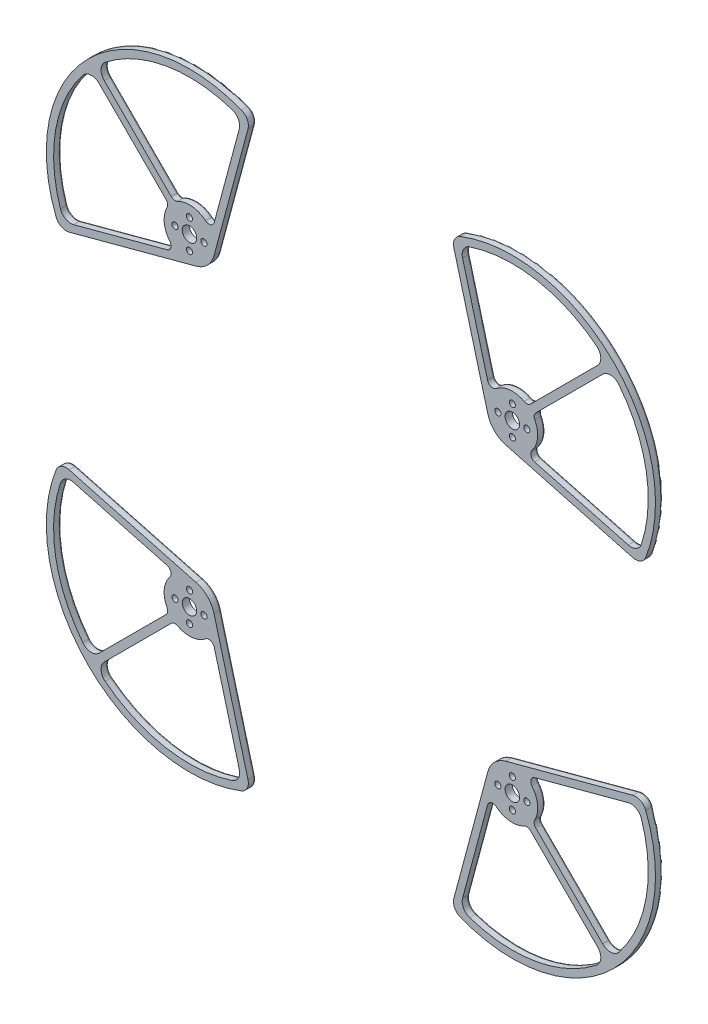
SolidWorks part; units mm, degrees
ref_plane "前视基准面" through (0, 0, 0) normal (0, 0, 1) x (1, 0, 0)
ref_plane "上视基准面" through (0, 0, 0) normal (0, 1, 0) x (1, 0, 0)
ref_plane "右视基准面" through (0, 0, 0) normal (1, 0, 0) x (0, 0, -1)
sketch "草图2" plane through (0, 0, -56.57) normal (0, 0, 1) x (1, 0, 0)
  line L0 (85.472, -75.5725) -> (160.5723, -55.4494)
  line L1 (0, 0) -> (89.0955, -89.0955) construction
  line L2 (75.5725, -85.472) -> (55.4494, -160.5723)
  line L3 (95.9714, -76.9003) -> (158.3049, -60.1981)
  line L4 (86.5073, -79.4362) -> (161.6076, -59.3131) construction
  line L5 (89.0955, -89.0955) -> (144.9569, -144.9569) construction
  line L6 (87.6812, -90.5097) -> (143.5248, -146.3532)
  line L7 (90.5097, -87.6812) -> (146.3532, -143.5248)
  line L8 (89.0955, -89.0955) -> (149.2055, -149.2055) construction
  line L9 (87.6812, -90.5097) -> (147.7913, -150.6197) construction
  line L10 (90.5097, -87.6812) -> (150.6197, -147.7913) construction
  line L11 (76.9003, -95.9714) -> (60.1981, -158.3049)
  circle A0 centre (89.0955, -89.0955) radius 75
  circle A1 centre (89.0955, -81.0955) radius 1.7 construction
  circle A2 centre (81.0955, -89.0955) radius 1.7 construction
  circle A3 centre (89.0955, -97.0955) radius 1.7 construction
  circle A4 centre (97.0955, -89.0955) radius 1.7 construction
  circle A5 centre (89.0955, -81.0955) radius 1.7
  circle A6 centre (81.0955, -89.0955) radius 1.7
  circle A7 centre (89.0955, -97.0955) radius 1.7
  circle A8 centre (97.0955, -89.0955) radius 1.7
  circle A9 centre (89.0955, -89.0955) radius 79
  circle A10 centre (89.0955, -89.0955) radius 14
  circle A11 centre (89.0955, -89.0955) radius 4 construction
  circle A12 centre (89.0955, -89.0955) radius 4
  dimension "D1" = 150
  dimension "D3" = 120
  dimension "D2" = 4
  dimension "D4" = 4
  dimension "D5" = 2
  dimension "D6" = 2
extrude "凸台-拉伸1" add sketch "草图2" along normal blind 4 contours A10 L3 A0 L0 | A10 L6 A0 L7 | A12 L7 A10 L6 A8 A7 A6 A5 | A12 L6 A10 L7 | A10 L2 A0 L11 | L2 A9 L6 A0 | L7 A9 L0 A0 | L6 A9 L7 A0
fillet "圆角1" radius 6 6 edges at (143.5238, -140.6954, -54.57) (140.6954, -143.5238, -54.57) (158.3049, -60.1981, -54.57) (160.5723, -55.4494, -54.57) (55.4494, -160.5723, -54.57) (60.1981, -158.3049, -54.57)
fillet "圆角2" radius 3 4 edges at (95.9714, -76.9003, -54.57) (76.9003, -95.9714, -54.57) (97.4792, -100.3076, -54.57) (100.3076, -97.4792, -54.57)
fillet "圆角3" radius 1 6 edges at (57.2351, -159.8231, -56.57) (66.1825, -120.5159, -56.57) (79.196, -79.196, -56.57) (120.5159, -66.1825, -56.57) (159.8231, -57.2351, -56.57) (144.9569, -144.9569, -56.57)
fillet "圆角4" radius 1 16 edges at (97.4952, -101.1535, -56.57) (87.7025, -103.026, -56.57) (77.4052, -99.3921, -56.57) (68.5172, -127.2577, -56.57) (62.1223, -157.445, -56.57) (102.1311, -162.9539, -56.57) (137.8898, -143.562, -56.57) (99.3921, -77.4052, -56.57) (103.026, -87.7025, -56.57) (101.1535, -97.4952, -56.57) (120.4849, -117.6565, -56.57) (143.562, -137.8898, -56.57) (162.9539, -102.1311, -56.57) (157.445, -62.1223, -56.57) (117.6565, -120.4849, -56.57) (127.2577, -68.5172, -56.57)
mirror "镜向1" about plane through (0, 0, 0) normal (0, 1, 0) of bodies 106
mirror "镜向2" about plane through (0, 0, 0) normal (1, 0, 0) of bodies 106 107
